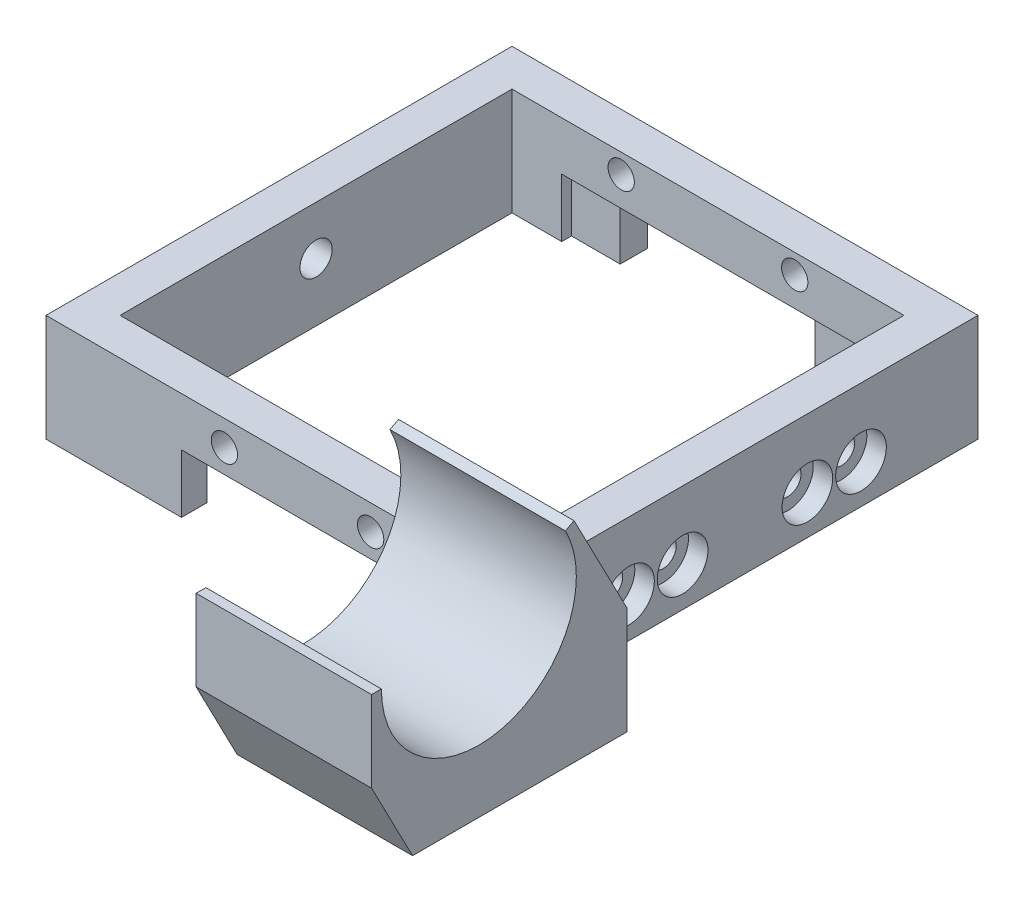
SolidWorks part; units mm, degrees
ref_plane "Front Plane" through (0, 0, 0) normal (0, 0, 1) x (1, 0, 0)
ref_plane "Top Plane" through (0, 0, 0) normal (0, 1, 0) x (1, 0, 0)
ref_plane "Right Plane" through (0, 0, 0) normal (1, 0, 0) x (0, 0, -1)
sketch "Sketch1" plane through (0, 0, 0) normal (0, 1, 0) x (1, 0, 0)
  line L0 (-20.1, 20.1) -> (20.1, -20.1) construction
  line L1 (-20.1, 20.1) -> (20.1, 20.1)
  line L2 (-20.1, 20.1) -> (-20.1, -20.1)
  line L3 (-20.1, -20.1) -> (20.1, -20.1)
  line L4 (20.1, 20.1) -> (20.1, -20.1)
  line L5 (-20.1, -20.1) -> (20.1, 20.1) construction
  line L6 (-23.9, 23.9) -> (-23.9, -23.9)
  line L7 (-23.9, -23.9) -> (23.9, -23.9)
  line L8 (23.9, 23.9) -> (23.9, -23.9)
  line L9 (-23.9, 23.9) -> (23.9, 23.9)
  point P4 (0, 0)
  dimension "D1" = 40.2
  dimension "D2" = 40.2
  dimension "D3" = 3.8
extrude "Boss-Extrude1" add sketch "Sketch1" along normal blind 11
sketch "Sketch3" plane through (0, 0, 23.9) normal (0, 0, 1) x (1, 0, 0)
  line L0 (-23.9, 0) -> (23.9, 0) construction
  line L1 (-10, 0) -> (10, 0)
  line L2 (-10, 0) -> (-10, 6)
  line L3 (-10, 6) -> (10, 6)
  line L4 (10, 0) -> (10, 6)
  point P6 (0, 6)
  dimension "D1" = 6
  dimension "D2" = 20
extrude "Cut-Extrude1" cut sketch "Sketch3" against normal through all
sketch "Sketch4" plane through (0, 0, -20.1) normal (0, 0, 1) x (1, 0, 0)
  line L1 (-10, 0) -> (-15, 0)
  line L2 (-10, 0) -> (-10, 6)
  line L3 (-10, 6) -> (-15, 6)
  line L4 (-15, 0) -> (-15, 6)
  line L5 (10, 0) -> (15, 0)
  line L6 (10, 0) -> (10, 6)
  line L7 (10, 6) -> (15, 6)
  line L8 (15, 0) -> (15, 6)
  dimension "D1" = 6
  dimension "D2" = 6
  dimension "D3" = 5
  dimension "D4" = 5
sketch "Sketch5" plane through (0, 0, 20.1) normal (0, 0, -1) x (-1, 0, 0)
  line L4 (-15, 0) -> (-10, 0)
  line L5 (-15, 6) -> (-15, 0)
  line L6 (-10, 6) -> (-15, 6)
  line L7 (-10, 0) -> (-10, 6)
  line L8 (10, 6) -> (10, 0)
  line L9 (10, 0) -> (20.1, 0)
  line L10 (20.1, 0) -> (20.1, 11)
  line L11 (20.1, 11) -> (-20.1, 11)
  line L12 (-20.1, 11) -> (-20.1, 0)
  line L13 (-20.1, 0) -> (-10, 0)
  line L14 (-10, 0) -> (-10, 6)
  line L15 (-10, 6) -> (10, 6)
  line L16 (10, 6) -> (10, 0)
  line L17 (10, 0) -> (20.1, 0)
  line L18 (20.1, 0) -> (20.1, 11)
  line L19 (20.1, 11) -> (-20.1, 11)
  line L20 (-20.1, 11) -> (-20.1, 0)
  line L21 (-20.1, 0) -> (-10, 0)
  line L22 (-10, 0) -> (-10, 6)
  line L23 (-10, 6) -> (10, 6)
  line L24 (-15, 0) -> (-10, 0)
  line L25 (-15, 6) -> (-15, 0)
  line L26 (-10, 6) -> (-15, 6)
  line L27 (-10, 0) -> (-10, 6)
  line L28 (10, 0) -> (15, 0)
  line L29 (15, 0) -> (15, 6)
  line L30 (15, 6) -> (10, 6)
  line L31 (10, 6) -> (10, 0)
  line L32 (10, 0) -> (15, 0)
  line L33 (15, 0) -> (15, 6)
  line L34 (15, 6) -> (10, 6)
  line L35 (10, 6) -> (10, 0)
  line M9 (10, 6) -> (10, 0)
  line M10 (10, 0) -> (20.1, 0)
  line M15 (-10, 0) -> (-10, 6)
  dimension "D1" = 0
  dimension "D2" = 0
  dimension "D3" = 0
extrude "Cut-Extrude2" cut sketch "Sketch4" against normal blind 1
sketch "Sketch6" plane through (0, 0, -23.9) normal (0, 0, -1) x (-1, 0, 0)
  line L0 (-8.9, 9) -> (8.9, 9) construction
  line L1 (23.9, 11) -> (23.9, 0) construction
  line L2 (-23.9, 11) -> (23.9, 11) construction
  circle A0 centre (-8.9, 9) radius 1.35
  circle A1 centre (8.9, 9) radius 1.35
  point P4 (0, 9)
  dimension "D3" = 2.7
  dimension "D4" = 2.7
  dimension "D1" = 15
  dimension "D2" = 2
extrude "Cut-Extrude4" cut sketch "Sketch6" against normal up to next
sketch "Sketch7" plane through (0, 0, 23.9) normal (0, 0, 1) x (1, 0, 0)
  line L0 (23.9, 11) -> (23.9, 0) construction
  circle A0 centre (9.4, 8.4128) radius 1.35
  circle A1 centre (-5.6, 8.4128) radius 1.35
  dimension "D1" = 2.7
  dimension "D2" = 2.7
  dimension "D3" = 14.5
  dimension "D4" = 15
extrude "Cut-Extrude5" cut sketch "Sketch7" against normal up to next
sketch "Sketch8" plane through (23.9, 0, 0) normal (1, 0, 0) x (0, 0, -1)
  line L0 (-23.9, 11) -> (-23.9, 0) construction
  line L1 (-23.9, 0) -> (23.9, 0) construction
  line L2 (0, 0) -> (0, 11) construction
  line L3 (-23.9, 11) -> (23.9, 11) construction
  circle A0 centre (-11.9, 4) radius 1.35
  circle A1 centre (-6.4, 4) radius 1.35
  circle A2 centre (6.4, 4) radius 1.35
  circle A3 centre (11.9, 4) radius 1.35
  dimension "D3" = 2.7
  dimension "D4" = 2.7
  dimension "D1" = 12
  dimension "D2" = 5.5
  dimension "D5" = 4
extrude "Cut-Extrude6" cut sketch "Sketch8" against normal up to next
sketch "Sketch9" plane through (-23.9, 0, 0) normal (-1, 0, 0) x (0, 0, 1)
  line L0 (-23.9, 0) -> (23.9, 0) construction
  circle A0 centre (0, 6) radius 1.65
  dimension "D2" = 3.3
  dimension "D1" = 6
extrude "Cut-Extrude7" cut sketch "Sketch9" against normal up to next
sketch "Sketch10" plane through (23.9, 0, 0) normal (1, 0, 0) x (0, 0, -1)
  line L3 (-20.1, 0) -> (-42.1, 0)
  line L6 (-23.9, 0) -> (23.9, 0) construction
  line L7 (-20.1, 0) -> (-20.1, 11)
  line L8 (-20.1, 11) -> (20.1, 11) construction
  line L9 (-20.1, 11) -> (20.1, 11) construction
  line L10 (-46.3, 8.0962) -> (-42.1, 0)
  line L12 (-20.1, 11) -> (-25.5357, 21.4782)
  line L13 (-46.3, 8.0962) -> (-46.3, 16.4128)
  line L14 (-46.3, 16.4128) -> (-45.3, 16.4128)
  line L15 (-26.4233, 21.0177) -> (-25.5357, 21.4782)
  circle A0 centre (-35.3, 16.4128) radius 8.5 construction
  arc A2 (-45.3, 16.4128) -> (-26.4233, 21.0177) centre (-35.3, 16.4128) ccw
  arc A3 (-46.3, 16.4128) -> (-25.5357, 21.4782) centre (-35.3, 16.4128) ccw
  line M6 (-23.9, 0) -> (23.9, 0)
  line M8 (23.9, 11) -> (-23.9, 11)
  line M9 (-23.9, 11) -> (-23.9, 0)
  dimension "D2" = 17
  dimension "D1" = 20
  dimension "D3" = 22
  dimension "D4" = 22
extrude "Boss-Extrude7" add sketch "Sketch10" along normal blind 8 and the other way blind 10 contours A3 L13 L3 L12 M9 M8 | L14 A3 L15 A2 | L7 M6 M8 M9
extrude "Cut-Extrude3" cut sketch "Sketch5" against normal blind 1.2 contours L26 L25 L21 M15 | L33 L34 M9 M10
sketch "Sketch11" plane through (23.9, 0, 0) normal (1, 0, 0) x (0, 0, -1)
  circle A0 centre (11.9, 4) radius 1.35 construction
  circle A1 centre (6.4, 4) radius 1.35 construction
  circle A3 centre (-6.4, 4) radius 1.35 construction
  circle A9 centre (-11.9, 4) radius 1.35 construction
  circle A10 centre (-11.9, 4) radius 1.35 construction
  circle A11 centre (-6.4, 4) radius 1.35 construction
  circle A12 centre (6.4, 4) radius 1.35 construction
  circle A13 centre (11.9, 4) radius 1.35 construction
  circle A14 centre (11.9, 4) radius 2.6
  circle A15 centre (6.4, 4) radius 2.6
  circle A16 centre (-6.4, 4) radius 2.6
  circle A17 centre (-11.9, 4) radius 2.6
  dimension "D1" = 5.2
  dimension "D2" = 5.2
  dimension "D3" = 5.2
  dimension "D4" = 5.2
extrude "Cut-Extrude8" cut sketch "Sketch11" against normal blind 2
equation "\"D3@Sketch11\"=\"D2@Sketch11\""
equation "\"D4@Sketch11\"=\"D2@Sketch11\""
